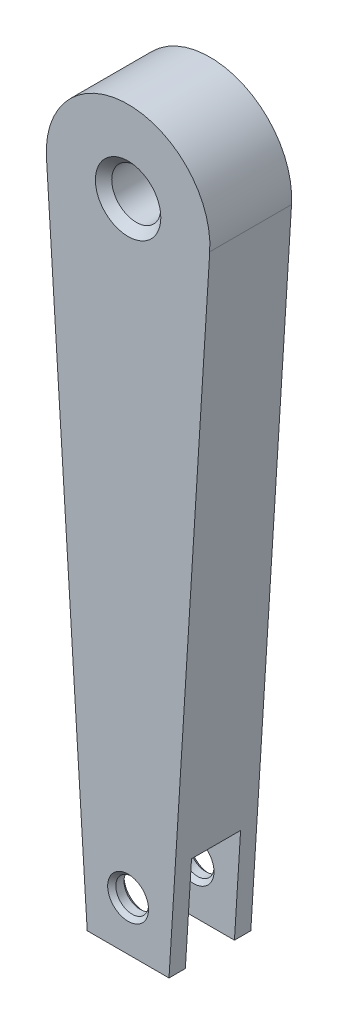
SolidWorks part; units mm, degrees
material "PE 高密度"
ref_plane "前视基准面" through (0, 0, 0) normal (0, 0, 1) x (1, 0, 0)
ref_plane "上视基准面" through (0, 0, 0) normal (0, 1, 0) x (1, 0, 0)
ref_plane "右视基准面" through (0, 0, 0) normal (1, 0, 0) x (0, 0, -1)
other "Configuration Table"
sketch "草图1" plane through (0, 0, 0) normal (0, 0, 1) x (1, 0, 0)
  circle A0 centre (0, 0) radius 10
  dimension "D1" = 20
extrude "凸台-拉伸1" add sketch "草图1" along normal blind 10
ref_plane "基准面1" through (0, 0, -2) normal (0, 0, 1) x (1, 0, 0)
sketch "草图2" plane through (0, 0, 0) normal (0, 0, 1) x (1, 0, 0)
  line L0 (-9.9804, -0.6262) -> (-5, -80)
  line L2 (0, 0) -> (0, -80) construction
  line L4 (-5, -80) -> (5, -80)
  line L5 (9.9804, -0.6262) -> (5, -80)
  circle A3 centre (0, 0) radius 10
  arc A4 (-9.9804, -0.6262) -> (9.9804, -0.6262) centre (0, 0) ccw
  point P12 (0, -80)
  dimension "D2" = 80
  dimension "D3" = 5
  dimension "D1" = 0
extrude "凸台-拉伸2" add sketch "草图2" along normal up to surface (10 mm away) up to face at (10, 0, 10)
ref_plane "基准面2" through (0, 0, 5) normal (0, 0, -1) x (-1, 0, 0)
ref_plane "基准面3" through (0, 0, 3) normal (0, 0, -1) x (-1, 0, 0)
sketch "草图3" plane through (0, 0, 3) normal (0, 0, -1) x (-1, 0, 0)
  circle A0 centre (0, 0) radius 3
  dimension "D1" = 6
extrude "切除-拉伸2" cut sketch "草图3" against normal through all both and the other way through all
sketch "草图7" plane through (0, 0, 0) normal (1, 0, 0) x (0, 0, -1)
  line L0 (-3, -128) -> (-3, -118.0885) construction
  line L1 (-2, -68) -> (-8, -68)
  line L2 (-2, -68) -> (-2, -84)
  line L3 (-2, -84) -> (-8, -84)
  line L4 (-8, -68) -> (-8, -84)
  line L5 (-2, -68) -> (-8, -84) construction
  line L6 (-2, -84) -> (-8, -68) construction
  line L10 (-5, -11) -> (-5, 11) construction
  line L12 (-10, -80) -> (0, -80) construction
  line L13 (-5, -80) -> (-5, -65.1701) construction
  point P11 (-5, -76)
  dimension "D1" = 6
  dimension "D2" = 12
  dimension "D3" = 16
extrude "切除-拉伸3" cut sketch "草图7" against normal through all both and the other way through all
sketch "草图8" plane through (0, 0, 10) normal (0, 0, 1) x (1, 0, 0)
  line L2 (0, 0) -> (0, -80) construction
  line L3 (-5, -80) -> (5, -80) construction
  circle A0 centre (0, -74) radius 2
  dimension "D1" = 4
  dimension "D2" = 6
extrude "切除-拉伸4" cut sketch "草图8" against normal through all and the other way through all
chamfer "倒角1" distance 1 angle 45 1 edges at (-3, 0, 10)
chamfer "倒角2" distance 0.5 angle 45 4 edges at (2, -74, 10) (2, -74, 8) (2, -74, 0) (0, -72, 2)
